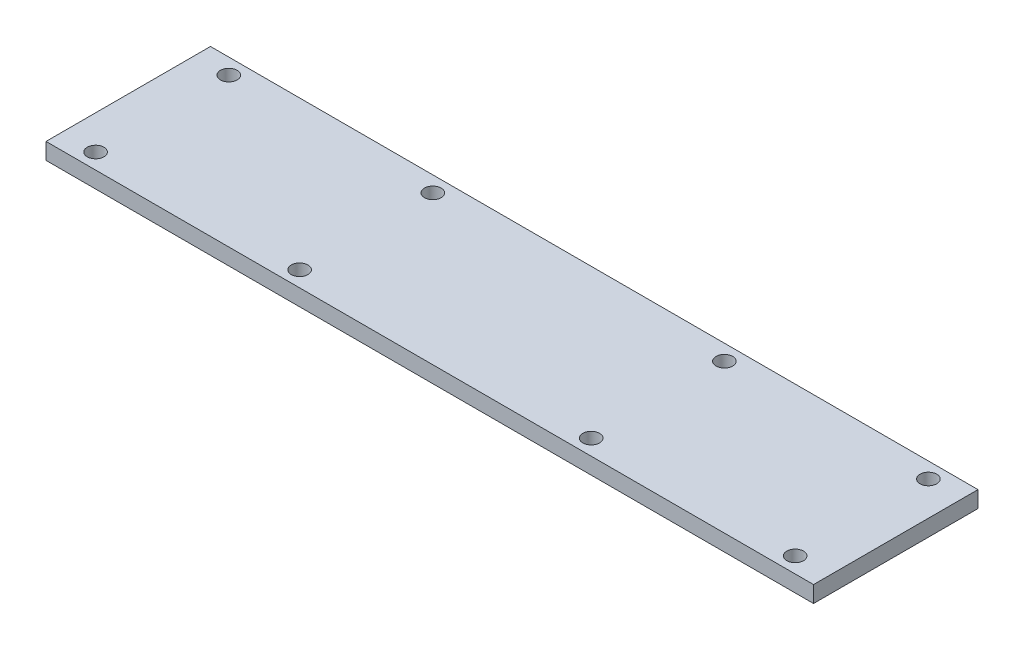
SolidWorks part; units mm, degrees
ref_plane "Front Plane" through (0, 0, 0) normal (0, 0, 1) x (1, 0, 0)
ref_plane "Top Plane" through (0, 0, 0) normal (0, 1, 0) x (1, 0, 0)
ref_plane "Right Plane" through (0, 0, 0) normal (1, 0, 0) x (0, 0, -1)
sketch "Sketch1" plane through (0, 0, 0) normal (0, 1, 0) x (1, 0, 0)
  line L0 (0, 0) -> (0, 16.7458) construction
  line L1 (-70, -15) -> (70, -15)
  line L2 (-70, -15) -> (-70, 15)
  line L3 (-70, 15) -> (70, 15)
  line L4 (70, -15) -> (70, 15)
  line L5 (-70, -15) -> (70, 15) construction
  line L6 (-70, 15) -> (70, -15) construction
  line L7 (0, 0) -> (-79.3516, 0) construction
  circle A0 centre (-63.8, 12.15) radius 1.525
  circle A1 centre (-63.8, -12.15) radius 1.525
  circle A2 centre (63.8, -12.15) radius 1.525
  circle A3 centre (63.8, 12.15) radius 1.525
  circle A4 centre (-26.595, 12.15) radius 1.525
  circle A5 centre (-26.595, -12.15) radius 1.525
  circle A6 centre (26.595, -12.15) radius 1.525
  circle A7 centre (26.595, 12.15) radius 1.525
  point P0 (0, 0)
  dimension "D4" = 3.05
  dimension "D1" = 140
  dimension "D2" = 30
  dimension "D3" = 6.2
  dimension "D5" = 12.15
  dimension "D7" = 37.205
  dimension "D6" = 2
extrude "Boss-Extrude1" add sketch "Sketch1" along normal blind 3
